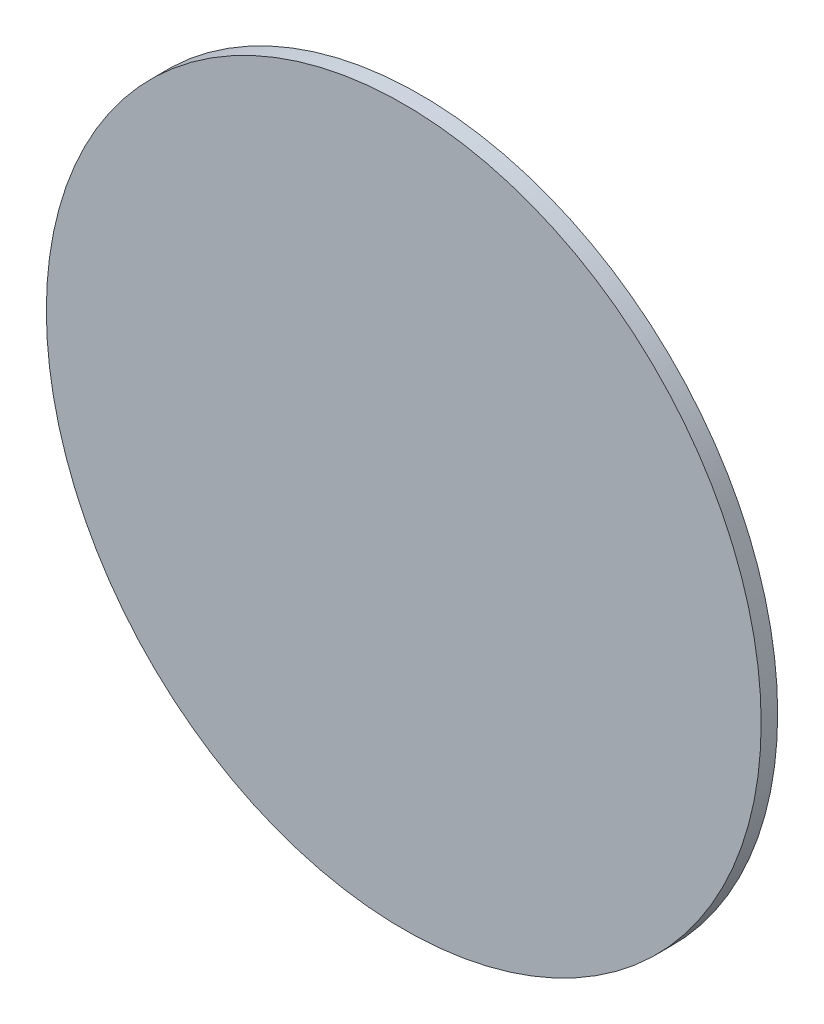
SolidWorks part; units mm, degrees
material "Verre"
ref_plane "Front Plane" through (0, 0, 0) normal (0, 0, 1) x (1, 0, 0)
ref_plane "Top Plane" through (0, 0, 0) normal (0, 1, 0) x (1, 0, 0)
ref_plane "Right Plane" through (0, 0, 0) normal (1, 0, 0) x (0, 0, -1)
sketch "Sketch1" plane through (0, 0, 0) normal (0, 0, 1) x (1, 0, 0)
  circle A1 centre (0, 0) radius 65
  dimension "D1" = 130
extrude "Boss-Extrude1" add sketch "Sketch1" along normal blind 3
